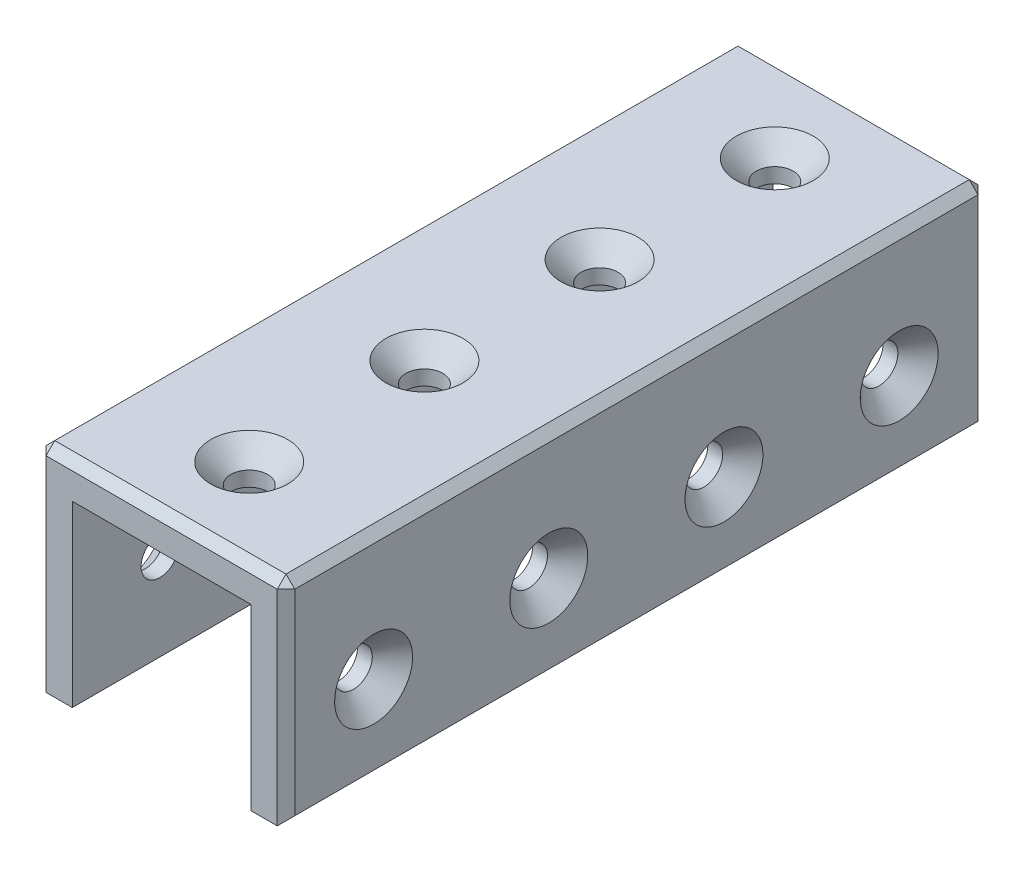
SolidWorks part; units mm, degrees
ref_plane "Front Plane" through (0, 0, 0) normal (0, 0, 1) x (1, 0, 0)
ref_plane "Top Plane" through (0, 0, 0) normal (0, 1, 0) x (1, 0, 0)
ref_plane "Right Plane" through (0, 0, 0) normal (1, 0, 0) x (0, 0, -1)
sketch "Sketch1" plane through (0, 0, 0) normal (0, 0, 1) x (1, 0, 0)
  line L0 (0, 0) -> (0, 20.4) construction
  line L1 (-10.2, 0) -> (-10.2, 20.4)
  line L2 (-10.2, 20.4) -> (10.2, 20.4)
  line L3 (10.2, 20.4) -> (10.2, 0)
  line L4 (10.2, 0) -> (14.2, 0)
  line L5 (14.2, 0) -> (14.2, 24.4)
  line L6 (14.2, 24.4) -> (-14.2, 24.4)
  line L7 (-14.2, 24.4) -> (-14.2, 0)
  line L8 (-14.2, 0) -> (-10.2, 0)
  dimension "D1" = 4
  dimension "D2" = 20.4
  dimension "D3" = 20.4
  dimension "D4" = 4
extrude "Boss-Extrude1" add sketch "Sketch1" along normal blind 80
sketch "Sketch2" plane through (14.2, 0, 0) normal (1, 0, 0) x (0, 0, -1)
  line L0 (-80, 10) -> (0, 10) construction
  line L1 (-80, 0) -> (-80, 24.4) construction
  line L2 (0, 0) -> (0, 24.4) construction
  line L3 (-80, 0) -> (0, 0) construction
  circle A0 centre (-50, 10) radius 2.15
  circle A1 centre (-70, 10) radius 2.15
  circle A2 centre (-30, 10) radius 2.15
  circle A3 centre (-10, 10) radius 2.15
  dimension "D2" = 4.3
  dimension "D4" = 20
  dimension "D5" = 20
  dimension "D6" = 10
  dimension "D1" = 10
  dimension "D3" = 20
extrude "Cut-Extrude1" cut sketch "Sketch2" against normal through all
sketch "Sketch3" plane through (0, 24.4, 0) normal (0, 1, 0) x (1, 0, 0)
  line L0 (0, 0) -> (0, -80) construction
  line L1 (14.2, -80) -> (-14.2, -80) construction
  line L2 (14.2, -12.15) -> (14.2, -7.85) construction
  line L3 (14.2, -32.15) -> (14.2, -27.85) construction
  line L4 (14.2, -52.15) -> (14.2, -47.85) construction
  line L5 (14.2, -72.15) -> (14.2, -67.85) construction
  line L6 (14.2, -12.15) -> (14.2, -7.85) construction
  line L7 (14.2, -32.15) -> (14.2, -27.85) construction
  line L8 (14.2, -52.15) -> (14.2, -47.85) construction
  line L9 (14.2, -72.15) -> (14.2, -67.85) construction
  line L10 (14.2, -10) -> (0, -10) construction
  line L11 (14.2, -30) -> (0, -30) construction
  line L12 (14.2, -50) -> (0, -50) construction
  line L13 (14.2, -70) -> (0, -70) construction
  circle A0 centre (0, -10) radius 2.1
  circle A1 centre (0, -30) radius 2.1
  circle A2 centre (0, -50) radius 2.1
  circle A3 centre (0, -70) radius 2.1
  dimension "D1" = 4.2
extrude "Cut-Extrude2" cut sketch "Sketch3" against normal through all
chamfer "Chamfer1" distance 2.3 angle 45 12 edges at (14.2, 12.15, 10) (14.2, 12.15, 30) (14.2, 12.15, 50) (14.2, 12.15, 70) (-2.1, 24.4, 10) (-2.1, 24.4, 30) (-2.1, 24.4, 50) (-2.1, 24.4, 70) (-14.2, 12.15, 70) (-14.2, 12.15, 50) (-14.2, 12.15, 30) (-14.2, 12.15, 10)
chamfer "Chamfer2" distance 1 angle 45 10 edges at (14.2, 0, 40) (-14.2, 0, 40) (-14.2, 12.2, 0) (0, 24.4, 0) (14.2, 12.2, 0) (14.2, 24.4, 40) (-14.2, 24.4, 40) (-14.2, 12.2, 80) (0, 24.4, 80) (14.2, 12.2, 80)
